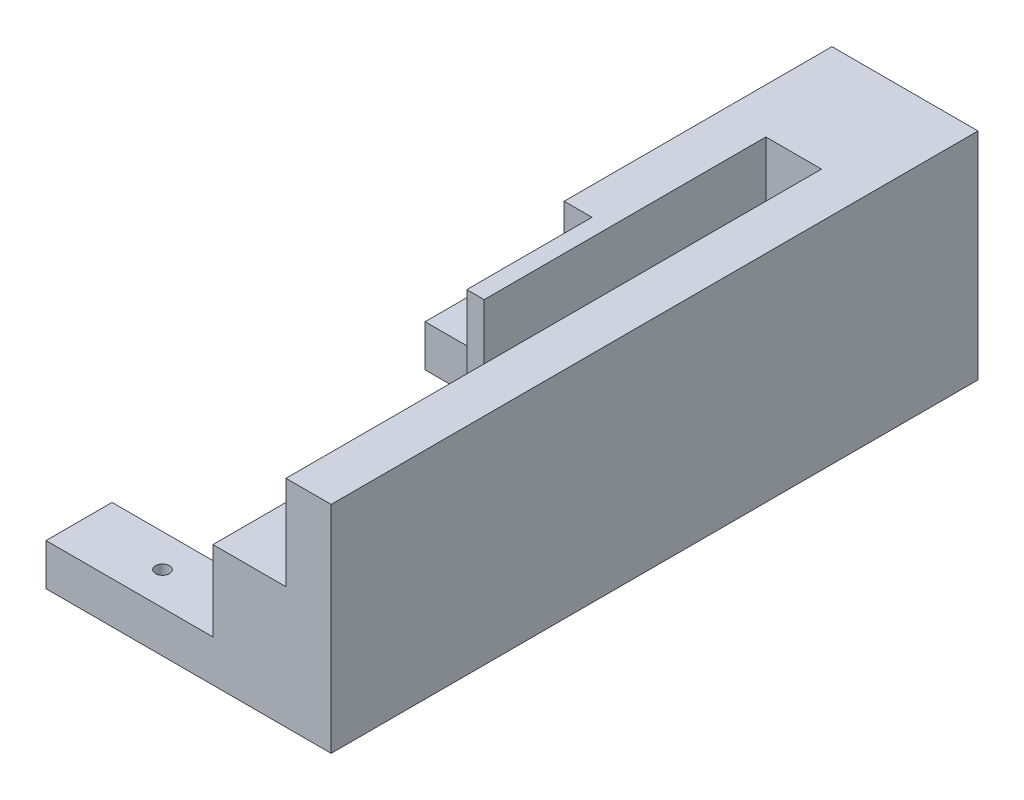
SolidWorks part; units mm, degrees
material "Haya"
ref_plane "Alzado" through (0, 0, 0) normal (0, 0, 1) x (1, 0, 0)
ref_plane "Planta" through (0, 0, 0) normal (0, 1, 0) x (1, 0, 0)
ref_plane "Vista lateral" through (0, 0, 0) normal (1, 0, 0) x (0, 0, -1)
sketch "Croquis1" plane through (0, 0, 0) normal (0, 1, 0) x (1, 0, 0)
  line L4 (-6, 11.25) -> (6, -11.25) construction
  line L5 (6, 11.25) -> (-6, -11.25) construction
  line L10 (-6, -16) -> (6, 16) construction
  line L11 (6, -16) -> (-6, 16) construction
  line L14 (-6, -5.5) -> (-6, -0.75)
  line L16 (13.5, -5.5) -> (13.5, 26.5)
  line L18 (-6, -0.75) -> (6, -0.75)
  line L19 (-6, 21.75) -> (-6, 26.5)
  line L21 (4, 26.5) -> (-6, 26.5)
  line L22 (-6, 21.75) -> (4, 21.75)
  line L23 (6, 11.25) -> (6, 21.75)
  line L24 (4, 21.75) -> (6, 21.75)
  line L25 (-6, -5.5) -> (4, -5.5)
  line L26 (6, -0.75) -> (6, 11.25)
  line L27 (4, -5.5) -> (13.5, -5.5)
  line L29 (4, 26.5) -> (4, 39)
  line L31 (4, 39) -> (13.5, 39)
  line L32 (13.5, 26.5) -> (13.5, 39)
  circle A2 centre (0, 24.125) radius 0.5
  circle A3 centre (0, -3.125) radius 0.5
  point P1 (0, 0)
  point P2 (0, 0)
  dimension "D3" = 44.5
  dimension "D4" = 4.75
  dimension "D13" = 1
  dimension "D5" = 1
  dimension "D2" = 22.5
  dimension "D7" = 2.375
  dimension "D12" = 12
  dimension "D14" = 4.75
  dimension "D15" = 2.375
extrude "Saliente-Extruir1" add sketch "Croquis1" along normal blind 3
sketch "Croquis2" plane through (0, 3, 0) normal (0, 1, 0) x (1, 0, 0)
  line L0 (13.5, -5.5) -> (13.5, 26.5)
  line L2 (4, 26.5) -> (4, 21.75)
  line L5 (11.25, -5.5) -> (11.25, 33)
  line L6 (11.25, -5.5) -> (13.5, -5.5)
  line L9 (-6, -5.5) -> (13.5, -5.5) construction
  line L10 (13.5, 26.5) -> (13.5, 39)
  line L11 (13.5, 39) -> (4, 39)
  line L12 (4, 39) -> (4, 26.5)
  line L14 (7.25, 33) -> (11.25, 33)
  line L15 (7.25, 33) -> (7.25, 12.75)
  line L16 (6, 21.75) -> (4, 21.75)
  line L18 (6, 21.75) -> (6, 12.75)
  line L20 (6, 12.75) -> (7.25, 12.75)
  point P7 (6.625, 12.75)
  dimension "D1" = 6
  dimension "D2" = 4
  dimension "D3" = 2.25
  dimension "D4" = 2
  dimension "D5" = 9
extrude "Saliente-Extruir2" add sketch "Croquis2" along normal blind 11
sketch "Croquis3" plane through (0, 3, 0) normal (0, 1, 0) x (1, 0, 0)
  line L3 (11.25, -5.5) -> (11.25, 33)
  line L4 (11.25, 33) -> (7.25, 33)
  line L5 (7.25, 33) -> (7.25, 12.75)
  line L11 (6, 12.75) -> (7.25, 12.75)
  line L12 (6, 12.75) -> (6, -5.5)
  line L13 (11.25, -5.5) -> (6, -5.5)
  dimension "D1" = 18.25
extrude "Saliente-Extruir3" add sketch "Croquis3" along normal blind 5.75
sketch "Croquis4" plane through (0, 0, -39) normal (0, 0, -1) x (-1, 0, 0)
  circle A0 centre (-9.87, 11.055) radius 2
  circle A1 centre (-9.87, 5.555) radius 1
  circle A2 centre (-9.87, 2.055) radius 1
  dimension "D3" = 4
  dimension "D4" = 2
  dimension "D5" = 2
  dimension "D1" = 3.63
  dimension "D2" = 2.945
  dimension "D7" = 5.5
  dimension "D8" = 3.5
extrude "Cortar-Extruir1" cut sketch "Croquis4" against normal blind 4
sketch "Croquis6" plane through (0, 0, -35) normal (0, 0, -1) x (-1, 0, 0)
  circle A0 centre (-9.87, 11.055) radius 2
  circle A1 centre (-9.87, 5.555) radius 1
  circle A2 centre (-9.87, 2.055) radius 1
extrude "Saliente-Extruir5" add sketch "Croquis6" along normal blind 4
sketch "Croquis8" plane through (0, 14, 0) normal (0, 1, 0) x (1, 0, 0)
  line L0 (4, 39) -> (4, 21.75)
  line L1 (4, 21.75) -> (6, 21.75)
  line L2 (6, 21.75) -> (6, 12.75)
  line L3 (6, 12.75) -> (7.25, 12.75)
  line L4 (7.25, 12.75) -> (7.25, 33)
  line L5 (7.25, 33) -> (11.25, 33)
  line L6 (11.25, 33) -> (11.25, -5.5)
  line L7 (11.25, -5.5) -> (13.5, -5.5)
  line L8 (13.5, -5.5) -> (13.5, 39)
  line L9 (13.5, 39) -> (4, 39)
extrude "Saliente-Extruir6" add sketch "Croquis8" along normal blind 1.5
sketch "Croquis9" plane through (13.5, 0, 0) normal (1, 0, 0) x (0, 0, -1)
  line L0 (-5.5, 15.5) -> (-5.5, 0)
  line L1 (-5.5, 0) -> (39, 0)
  line L2 (39, 0) -> (39, 15.5)
  line L3 (39, 15.5) -> (-5.5, 15.5)
extrude "Saliente-Extruir7" add sketch "Croquis9" along normal blind 1
sketch "Croquis11" plane through (0, 0, -39) normal (0, 0, -1) x (-1, 0, 0)
  line L0 (-14.5, 15.5) -> (-14.5, 0)
  line L1 (-14.5, 0) -> (-4, 0)
  line L2 (-4, 0) -> (-4, 15.5)
  line L3 (-4, 15.5) -> (-14.5, 15.5)
extrude "Saliente-Extruir10" add sketch "Croquis11" along normal blind 2
sketch "Croquis7" plane through (0, 0, -41) normal (0, 0, -1) x (-1, 0, 0)
  circle A0 centre (-9.87, 11.055) radius 2.25
  dimension "D1" = 4.5
extrude "Cortar-Extruir2" cut sketch "Croquis7" against normal blind 2
sketch "Sketch1" plane through (0, 0, -41) normal (0, 0, -1) x (-1, 0, 0)
  point P0 (-9.87, 11.055)
  point P1 (-9.87, 11.055)
  point P3 (0, 0)
